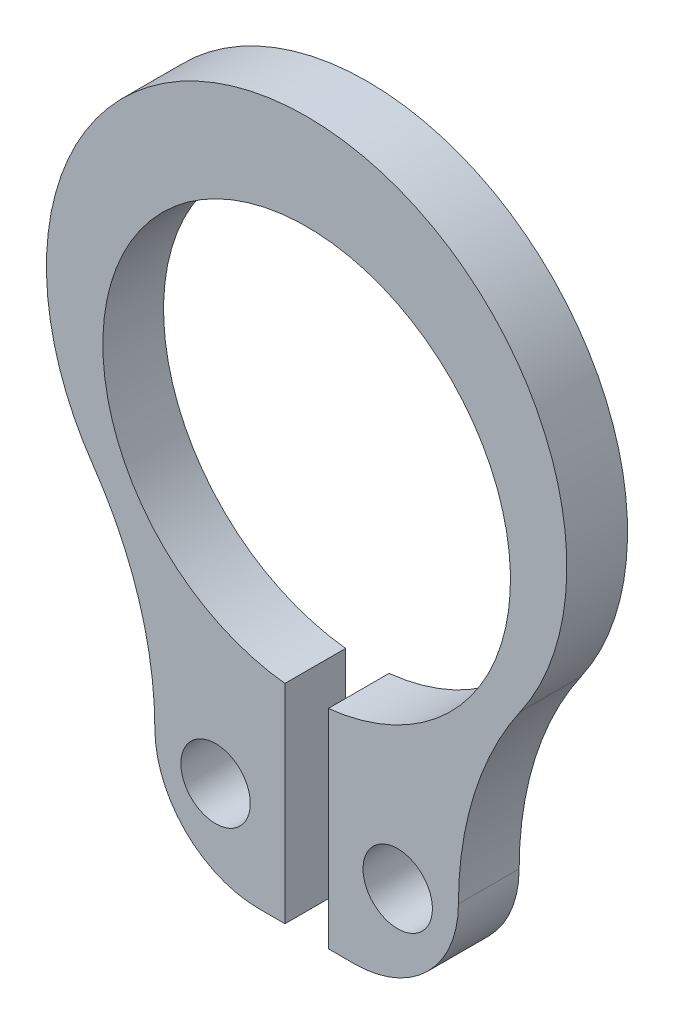
SolidWorks part; units mm, degrees
ref_plane "前视基准面" through (0, 0, 0) normal (0, 0, 1) x (1, 0, 0)
ref_plane "上视基准面" through (0, 0, 0) normal (0, 1, 0) x (1, 0, 0)
ref_plane "右视基准面" through (0, 0, 0) normal (1, 0, 0) x (0, 0, -1)
sketch "草图1" plane through (0, 0, 0) normal (0, 0, 1) x (1, 0, 0)
  line L0 (0, 0) -> (0, -9.258) construction
  line L1 (-0.25, -2.3367) -> (-0.25, -4.7367)
  line L2 (0.25, -4.7367) -> (0.55, -4.7367)
  line L3 (-0.25, -4.7367) -> (-0.55, -4.7367)
  line L4 (0.25, -2.3367) -> (0.25, -4.7367)
  arc A0 (0.25, -2.3367) -> (-0.25, -2.3367) centre (0, 0) ccw
  arc A1 (0.55, -4.7367) -> (1.75, -3.5379) centre (0.55, -3.5367) ccw
  arc A2 (1.75, -3.5379) -> (2.4643, -1.2609) centre (5.75, -3.5422) cw
  arc A3 (2.4643, -1.2609) -> (-2.4643, -1.2609) centre (0, 0.45) ccw
  circle A4 centre (-1.05, -3.7367) radius 0.4
  circle A5 centre (1.05, -3.7367) radius 0.4
  arc A6 (-0.55, -4.7367) -> (-1.75, -3.5379) centre (-0.55, -3.5367) cw
  arc A7 (-1.75, -3.5379) -> (-2.4643, -1.2609) centre (-5.75, -3.5422) ccw
  dimension "D1" = 4.7
  dimension "D2" = 1.1
  dimension "D3" = 2.4
  dimension "D8" = 0.8
  dimension "D11" = 1.2
  dimension "D4" = 3
  dimension "D6" = 1
  dimension "D7" = 0.8
  dimension "D9" = 4
  dimension "D5" = 0.25
  dimension "D10" = 0.3
extrude "凸台-拉伸1" add sketch "草图1" along normal blind 0.7
